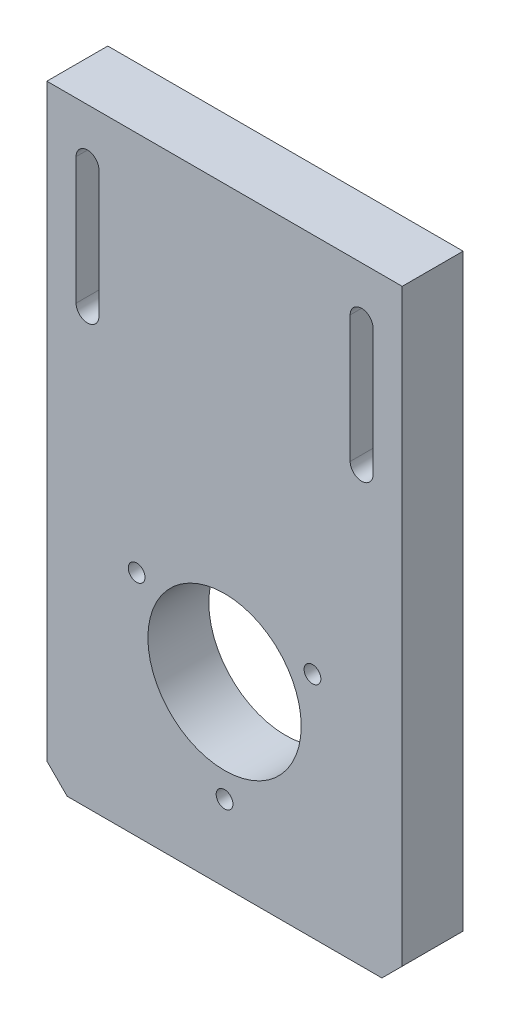
SolidWorks part; units mm, degrees
ref_plane "Front Plane" through (0, 0, 0) normal (0, 0, 1) x (1, 0, 0)
ref_plane "Top Plane" through (0, 0, 0) normal (0, 1, 0) x (1, 0, 0)
ref_plane "Right Plane" through (0, 0, 0) normal (1, 0, 0) x (0, 0, -1)
sketch "草图1" plane through (0, 0, 0) normal (0, 0, 1) x (1, 0, 0)
  line L1 (-38.5, -42.5) -> (23.5, -42.5)
  line L2 (-42.5, -38.5) -> (-42.5, 77.5)
  line L3 (-42.5, 77.5) -> (27.5, 77.5)
  line L4 (27.5, -38.5) -> (27.5, 77.5)
  line L8 (-42.5, -38.5) -> (-38.5, -42.5)
  line L9 (23.5, -42.5) -> (27.5, -38.5)
  point P0 (-42.5, -42.5)
  point P3 (27.5, -42.5)
  dimension "D1" = 70
extrude "凸台-拉伸1" add sketch "草图1" along normal blind 12
sketch "草图2" plane through (0, 0, 12) normal (0, 0, 1) x (1, 0, 0)
  line L0 (-38.5, -42.5) -> (23.5, -42.5) construction
  line L1 (27.5, -38.5) -> (27.5, 77.5) construction
  circle A4 centre (-7.5, -7.5) radius 15.1
  dimension "D1" = 30.2
  dimension "D2" = 35
  dimension "D3" = 35
extrude "切除-拉伸1" cut sketch "草图2" against normal through all
hole_wizard "M4x0.7 螺纹孔1" positions "草图6" profile "草图5" tap size "M4x0.7" standard "Ansi Metric" end condition through all
sketch "草图6" plane through (0, 0, 12) normal (0, 0, 1) x (1, 0, 0)
  line L0 (-42.5, 77.5) -> (-42.5, -38.5) construction
  circle A0 centre (-7.5, -7.5) radius 15.1 construction
  point P0 (-7.5, -27.5)
  point P32 (-24.8205, 2.5)
  point P33 (9.8205, 2.5)
  dimension "D1" = 20
  dimension "D3" = 35
cosmetic thread "孔螺蚊线1" parameters "D2"=4
cosmetic thread "孔螺蚊线2" parameters "D2"=4
sketch "草图5" plane through (-7.5, -27.5, 12) normal (1, 0, 0) x (0, -1, 0)
  line L0 (0, 0) -> (0, 12)
  line L1 (0, 12) -> (1.65, 12)
  line L2 (1.65, 12) -> (1.65, 0)
  line L5 (1.65, 0) -> (0, 0)
  line L11 (0, -6.35) -> (0, 107.95) construction
  dimension "通孔螺纹孔钻头直径" = 3.3
  dimension "通孔螺纹孔钻头深度" = 12
cosmetic thread "孔螺蚊线4" parameters "D2"=4
sketch "草图7" plane through (0, 0, 12) normal (0, 0, 1) x (1, 0, 0)
  line L0 (-34.5, 67.5) -> (-34.5, 42.5) construction
  line L1 (-32.25, 67.5) -> (-32.25, 42.5)
  line L2 (-36.75, 67.5) -> (-36.75, 42.5)
  line L3 (27.5, 77.5) -> (-42.5, 77.5) construction
  line L4 (-42.5, 77.5) -> (-42.5, -38.5) construction
  line L5 (-7.5, 77.5) -> (-7.5, 32.5576) construction
  line L6 (19.5, 67.5) -> (19.5, 42.5) construction
  line L7 (17.25, 67.5) -> (17.25, 42.5)
  line L8 (21.75, 67.5) -> (21.75, 42.5)
  arc A0 (-32.25, 67.5) -> (-36.75, 67.5) centre (-34.5, 67.5) ccw
  arc A1 (-36.75, 42.5) -> (-32.25, 42.5) centre (-34.5, 42.5) ccw
  arc A2 (17.25, 67.5) -> (21.75, 67.5) centre (19.5, 67.5) cw
  arc A3 (21.75, 42.5) -> (17.25, 42.5) centre (19.5, 42.5) cw
  point P2 (-34.5, 55)
  point P16 (19.5, 55)
  dimension "D1" = 2.25
  dimension "D3" = 10
  dimension "D4" = 8
  dimension "D2" = 25
extrude "切除-拉伸2" cut sketch "草图7" against normal through all
